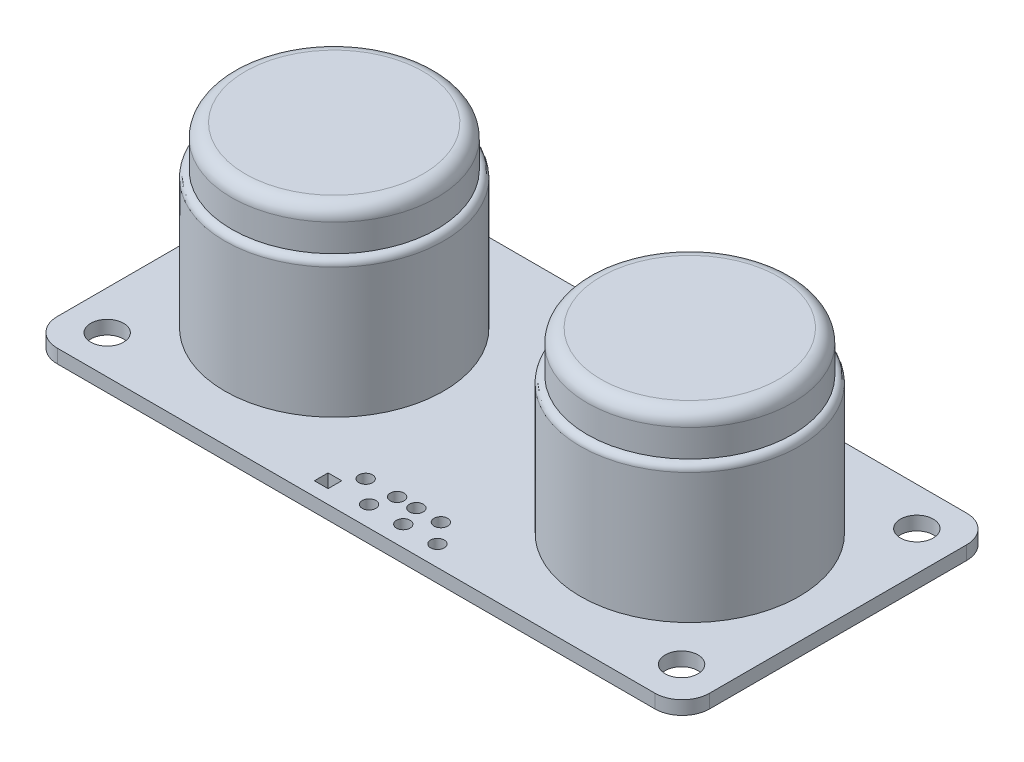
SolidWorks part; units mm, degrees
ref_plane "前视基准面" through (0, 0, 0) normal (0, 0, 1) x (1, 0, 0)
ref_plane "上视基准面" through (0, 0, 0) normal (0, 1, 0) x (1, 0, 0)
ref_plane "右视基准面" through (0, 0, 0) normal (1, 0, 0) x (0, 0, -1)
other "Configuration Table"
ref_plane "基准面1" through (0, 0, 0) normal (0, -1, 0) x (1, 0, 0)
sketch "草图1" plane through (0, 0, 0) normal (0, -1, 0) x (1, 0, 0)
  line L0 (-23.85, -11.4) -> (23.85, -11.4)
  line L1 (23.85, -11.4) -> (23.85, 11.4)
  line L2 (23.85, 11.4) -> (-23.85, 11.4)
  line L3 (-23.85, 11.4) -> (-23.85, -11.4)
extrude "凸台-拉伸1" add sketch "草图1" against normal blind 1
sketch "草图2" plane through (0, 1, 0) normal (0, 1, 0) x (-1, 0, 0)
  line L0 (4.05, 9.4) -> (4.05, 10.4)
  line L1 (4.05, 10.4) -> (3.05, 10.4)
  line L2 (3.05, 10.4) -> (3.05, 9.4)
  line L3 (3.05, 9.4) -> (4.05, 9.4)
extrude "切除-拉伸1" cut sketch "草图2" against normal through all
ref_plane "基准面2" through (0, 0, 0) normal (0, 0, -1) x (-1, 0, 0)
sketch "草图3" plane through (0, 0, 0) normal (0, 0, -1) x (-1, 0, 0)
  line L0 (-21, 1) -> (-13, 1)
  line L1 (-13, 1) -> (-13, 14)
  line L2 (-13, 14) -> (-20.5, 14)
  line L3 (-20.5, 14) -> (-20.5, 11)
  line L4 (-21, 10.5) -> (-21, 1)
  line L5 (-13, 1) -> (-13, 14) construction
  arc A0 (-20.5, 11) -> (-21, 10.5) centre (-20.5, 10.5) ccw
revolve "旋转1" add sketch "草图3" angle 360 about L5
sketch "草图4" plane through (0, 0, 0) normal (0, 0, -1) x (-1, 0, 0)
  line L0 (5, 1) -> (13, 1)
  line L1 (13, 1) -> (13, 14)
  line L2 (13, 14) -> (5.5, 14)
  line L3 (5.5, 14) -> (5.5, 11)
  line L4 (5, 10.5) -> (5, 1)
  line L5 (13, 1) -> (13, 14) construction
  arc A0 (5.5, 11) -> (5, 10.5) centre (5.5, 10.5) ccw
  dimension "D1" = 0.5
revolve "旋转2" add sketch "草图4" angle 360 about L5
hole_wizard "Ø1.0 (1) 直径孔1" positions "草图6" profile "草图5" hole size "Ø1.0" standard "ANSI Metric"
sketch "草图6" plane through (0, 1, 0) normal (0, 1, 0) x (1, 0, 0)
  point P0 (-0.55, -9.9)
  point P1 (1.95, -9.9)
  point P2 (4.45, -9.9)
  point P3 (-2.3, -8.4)
  point P4 (0, -8.4)
  point P5 (3.2, -8.4)
  point P6 (1.4073, -8.4)
sketch "草图5" plane through (-0.55, 1, 9.9) normal (1, 0, 0) x (0, 0, 1)
  line L0 (0, 0) -> (0, 1)
  line L1 (0, 1) -> (0.5, 1)
  line L2 (0.5, 1) -> (0.5, 0)
  line L5 (0.5, 0) -> (0, 0)
  line L11 (0, -6.35) -> (0, 107.95) construction
  dimension "通孔孔直径" = 1
  dimension "通孔孔深度" = 1
hole_wizard "Ø2.4 (2.4) 直径孔1" positions "草图8" profile "草图7" hole size "Ø2.4" standard "ANSI Metric"
sketch "草图8" plane through (0, 0, 0) normal (0, -1, 0) x (-1, 0, 0)
  point P0 (21, 8.6)
  point P1 (-21, 8.6)
  point P2 (-21, -8.6)
  point P3 (21, -8.6)
sketch "草图7" plane through (-21, 0, -8.6) normal (1, 0, 0) x (0, 0, -1)
  line L0 (0, 0) -> (0, 14)
  line L1 (0, 14) -> (1.2, 14)
  line L2 (1.2, 14) -> (1.2, 0)
  line L5 (1.2, 0) -> (0, 0)
  line L11 (0, -6.35) -> (0, 107.95) construction
  dimension "通孔孔直径" = 2.4
  dimension "通孔孔深度" = 14
fillet "圆角1" radius 1 2 edges at (13, 14, 7.5) (-13, 14, 7.5)
fillet "圆角2" radius 2 4 edges at (-23.85, 0.5, -11.4) (23.85, 0.5, 11.4) (23.85, 0.5, -11.4) (-23.85, 0.5, 11.4)
